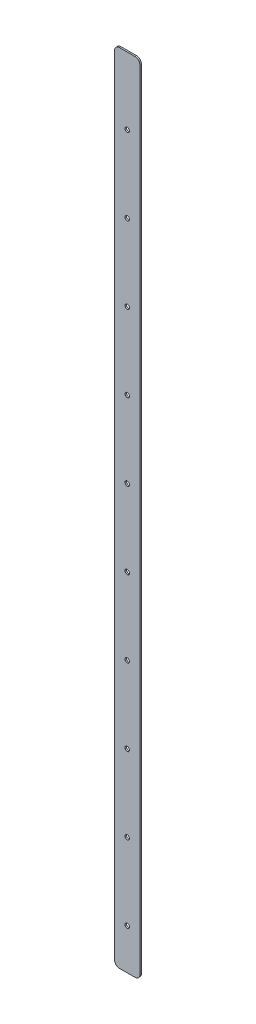
SolidWorks part; units mm, degrees
material "AISI 304"
ref_plane "Спереди" through (0, 0, 0) normal (0, 0, 1) x (1, 0, 0)
ref_plane "Сверху" through (0, 0, 0) normal (0, 1, 0) x (1, 0, 0)
ref_plane "Справа" through (0, 0, 0) normal (1, 0, 0) x (0, 0, -1)
other "Configuration Table"
sketch "Эскиз1" plane through (0, 0, 0) normal (0, 0, 1) x (1, 0, 0)
  line L1 (-25, -781) -> (25, -781)
  line L2 (-25, -781) -> (-25, 781)
  line L3 (-25, 781) -> (25, 781)
  line L4 (25, -781) -> (25, 781)
  line L5 (0, 781) -> (0, -781) construction
  line L6 (-25, 0) -> (25, 0) construction
  point P0 (0, 0)
  dimension "D1" = 1562
  dimension "D2" = 50
extrude "Бобышка-Вытянуть1" add sketch "Эскиз1" along normal blind 3
fillet "Скругление1" radius 10 4 edges at (25, -781, 1.5) (-25, -781, 1.5) (-25, 781, 1.5) (25, 781, 1.5)
sketch "Эскиз2" plane through (0, 0, 3) normal (0, 0, 1) x (1, 0, 0)
  line L0 (-15, -781) -> (15, -781) construction
  circle A0 centre (0, -701) radius 4.4
  dimension "D1" = 8.8
  dimension "D2" = 80
extrude "Вырез-Вытянуть1" cut sketch "Эскиз2" against normal blind 10
pattern_linear "Линейный массив1" count 10 spacing 150 along (0, 1, 0) of "Вырез-Вытянуть1"
